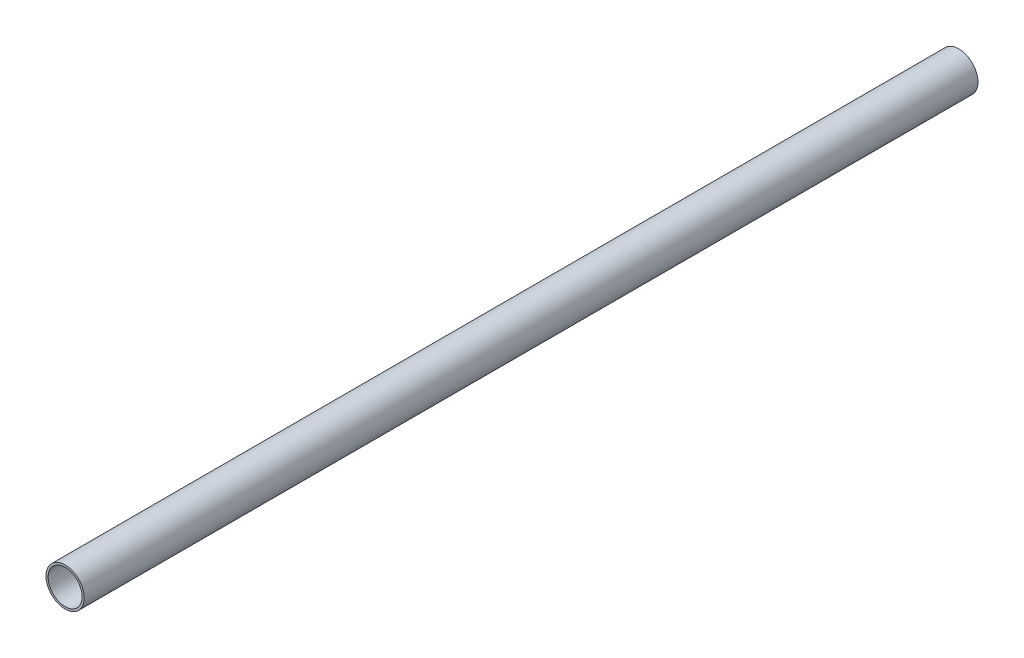
SolidWorks part; units mm, degrees
material "Tubi carbonio"
ref_plane "Piano frontale" through (0, 0, 0) normal (0, 0, 1) x (1, 0, 0)
ref_plane "Piano superiore" through (0, 0, 0) normal (0, 1, 0) x (1, 0, 0)
ref_plane "Piano destro" through (0, 0, 0) normal (1, 0, 0) x (0, 0, -1)
sketch "Schizzo1" plane through (0, 0, 0) normal (0, 0, 1) x (1, 0, 0)
  circle A0 centre (0, 0) radius 8
  circle A1 centre (0, 0) radius 9
  dimension "D1" = 16
  dimension "D2" = 18
extrude "Estrusione-Estrusione1" add sketch "Schizzo1" along normal blind 420
